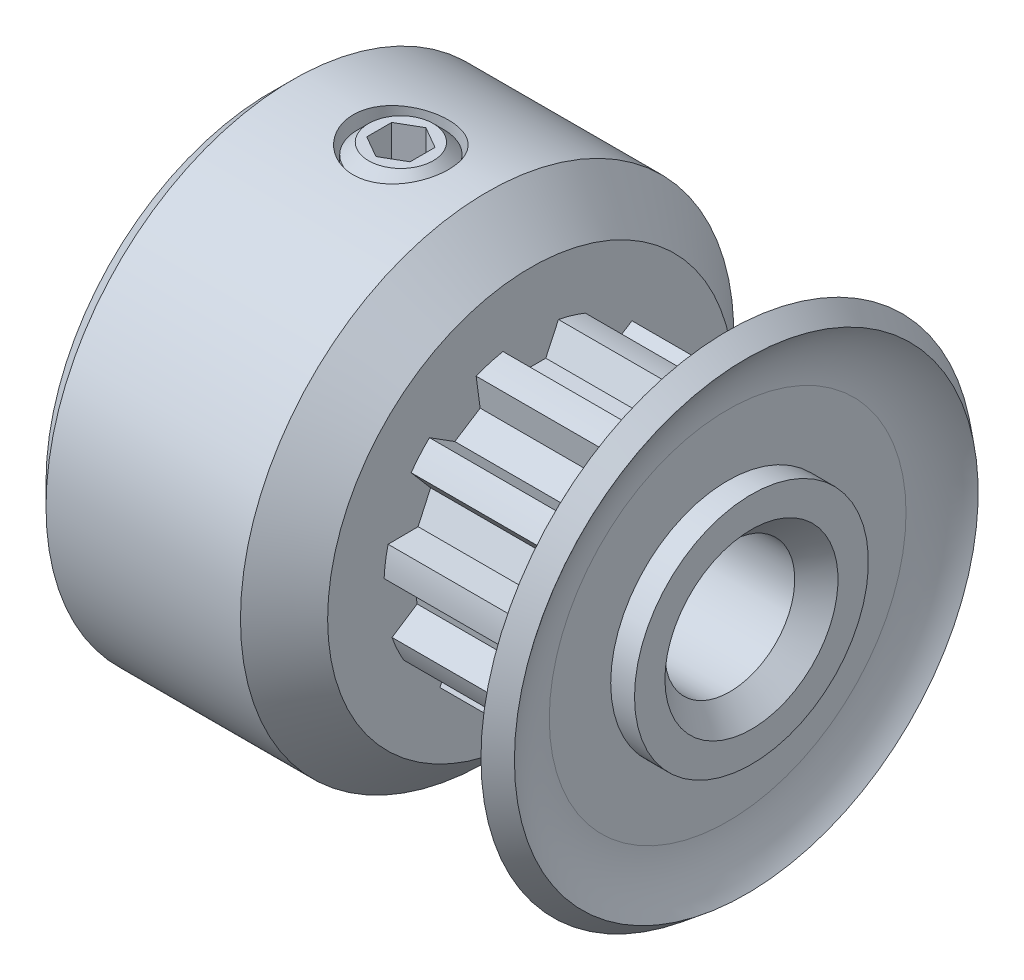
SolidWorks part; units mm, degrees
ref_plane "Front Plane" through (0, 0, 0) normal (0, 0, 1) x (1, 0, 0)
ref_plane "Top Plane" through (0, 0, 0) normal (0, 1, 0) x (1, 0, 0)
ref_plane "Right Plane" through (0, 0, 0) normal (1, 0, 0) x (0, 0, -1)
sketch "Sketch2" plane through (0, 0, 0) normal (1, 0, 0) x (0, 0, -1)
  line L3 (0, 0) -> (0, 2.7245) construction
  line L6 (0, -3.2325) -> (0, -3.55) construction
  line L7 (-0.5715, 3.1816) -> (-0.348, 2.7022)
  line L8 (0.5715, 3.1816) -> (0.348, 2.7022)
  line L9 (-0.5715, 3.1816) -> (-0.6408, 3.3302)
  line L10 (0.5715, 3.1816) -> (0.6408, 3.3302)
  line L12 (-0.348, 2.7022) -> (0.348, 2.7022)
  line L14 (0, 3.2325) -> (0, 3.55) construction
  line L15 (0, 0) -> (0, -1.143) construction
  circle A0 centre (0, 0) radius 3.55 construction
  circle A1 centre (0, 0) radius 2.7245 construction
  circle A2 centre (0, 0) radius 3.2325 construction
  arc A7 (0.6408, 3.3302) -> (-0.6408, 3.3302) centre (0, 0) ccw
  point P5 (0, 3.3912)
  dimension "D3" = 0.3175
  dimension "D1" = 50
sketch "Sketch1" plane through (0, 0, 0) normal (0, 0, 1) x (1, 0, 0)
  line L0 (-5.55, 0) -> (5.55, 0) construction
  line L1 (-5.55, 1.5) -> (5.55, 1.5)
  line L2 (-5.55, 1.5) -> (-5.55, 5.7)
  line L3 (-5.55, 5.7) -> (-0.557, 5.7)
  line L4 (-0.557, 5.7) -> (0.45, 4.693)
  line L5 (0.45, 4.693) -> (0.45, 3.55)
  line L6 (0.45, 3.55) -> (4.45, 3.55)
  line L7 (4.45, 3.55) -> (4.45, 4.1215)
  line L8 (4.45, 3.55) -> (5.55, 3.55) construction
  line L9 (5, 5.7) -> (5.55, 5.7)
  line L10 (5.55, 5.7) -> (5.55, 1.5)
  line L11 (5, 3.55) -> (5, 5.7) construction
  line L12 (-3.0535, 5.7) -> (-3.0535, 1.5) construction
  arc A0 (4.45, 4.1215) -> (5, 5.7) centre (6.9901, 4.1215) cw
  dimension "Bore Size" = 3
  dimension "Overall Width" = 11.1
  dimension "Inside Width" = 4
  dimension "Outside Width" = 5.1
  dimension "Hub Dia" = 11.4
  dimension "OD" = 11.4
  dimension "D1" = 45
  dimension "D2" = 7.1
  dimension "D3" = 1.143
  dimension "D4" = 0.5715
revolve "Revolve1" add sketch "Sketch1" angle 360 mid plane about L0
sketch "Sketch4" plane through (0.45, 0, 0) normal (1, 0, 0) x (0, 0, -1)
  circle A0 centre (0, 0) radius 3.3913
  circle A1 centre (0, 0) radius 3.55 construction
  circle A2 centre (0, 0) radius 3.55
extrude "Cut-Extrude2" cut sketch "Sketch4" along normal up to surface (4 mm away) up to face at (4.45, 0, 3.55)
sketch "Sketch3" plane through (0.45, 0, 0) normal (1, 0, 0) x (0, 0, -1)
  line L2 (-0.5715, 3.1816) -> (-0.348, 2.7022) construction
  line L3 (-0.348, 2.7022) -> (0.348, 2.7022) construction
  line L4 (0.5715, 3.1816) -> (0.348, 2.7022) construction
  line L5 (-0.6408, 3.3302) -> (-0.348, 2.7022)
  line L6 (-0.348, 2.7022) -> (0.348, 2.7022)
  line L7 (0.6408, 3.3302) -> (0.348, 2.7022)
  arc A1 (0.6408, 3.3302) -> (-0.6408, 3.3302) centre (0, 0) ccw construction
  arc A2 (0.6408, 3.3302) -> (-0.6408, 3.3302) centre (0, 0) ccw
extrude "Cut-Extrude1" cut sketch "Sketch3" along normal up to surface (4 mm away)
pattern_circular "CirPattern1" count 11 over 360 about axis through (0, 0, 0) along (1, 0, 0) of "Cut-Extrude1"
sketch "Sketch5" plane through (0, 0, 0) normal (0, 1, 0) x (1, 0, 0)
  line L0 (-5.55, 5.7) -> (-5.55, -5.7) construction
  line L1 (4.45, 4.1215) -> (4.45, -4.1215) construction
  line L2 (5.55, 5.7) -> (5.55, -5.7) construction
  line L3 (0.45, 4.693) -> (0.45, -4.693) construction
  line L4 (4.45, 4.1215) -> (4.45, -4.1215) construction
  line L5 (-5.55, 0) -> (5.55, 0) construction
  line L6 (-5.55, 0) -> (5.55, 0) construction
  point P0 (4.45, 0)
  point P14 (4.45, 0)
  point P15 (0.45, 0)
  dimension "D1" = 11.4
  dimension "D2" = 11.4
sketch "Sketch6" plane through (0, 0, 0) normal (0, 1, 0) x (1, 0, 0)
  line L0 (-5.55, 0) -> (-3.55, 0) construction
  line L1 (-5.55, 5.7) -> (-5.55, -5.7) construction
  line L2 (0.45, 0) -> (-1.55, 0) construction
  line L3 (0.45, -0.348) -> (0.45, 0.348) construction
  line L4 (-3.55, 0) -> (-2.55, 0) construction
  line L5 (-2.55, 0) -> (-3.2571, -0.7071) construction
  circle A0 centre (-2.55, 0) radius 1 construction
  circle A1 centre (-2.55, 0) radius 1.1
  point P13 (-3.2571, -0.7071)
  dimension "D1" = 0.1
  dimension "D2" = 45
  dimension "SS Dia" = 2
extrude "Cut-Extrude3" cut sketch "Sketch6" along normal through all
sketch "Sketch7" plane through (0, 0, 0) normal (0, 0, 1) x (1, 0, 0)
  line L0 (-3.296, 5.7) -> (-2.55, 5.7)
  line L1 (-3.55, 5.446) -> (-3.55, 2.135)
  line L2 (-3.55, 2.135) -> (-3.296, 1.881)
  line L3 (-3.296, 1.881) -> (-2.55, 1.881)
  line L4 (-2.55, 1.881) -> (-2.55, 5.7) construction
  line L6 (-3.55, 5.446) -> (-3.296, 5.7)
  line L7 (-5.55, 5.7) -> (-0.557, 5.7) construction
  line L8 (-2.55, 5.7) -> (-2.55, 1.881)
  point P0 (-3.55, 5.7)
  point P4 (-3.55, 1.881)
  dimension "D2" = 0.381
revolve "Revolve2" add sketch "Sketch7" angle 360 mid plane about L4
sketch "Sketch8" plane through (0, 5.7, 0) normal (0, 1, 0) x (1, 0, 0)
  line L0 (-2.55, 0) -> (-3.55, 0) construction
  line L1 (-2.55, 0.5774) -> (-3.05, 0.2887)
  line L2 (-3.05, 0.2887) -> (-3.05, -0.2887)
  line L3 (-3.05, -0.2887) -> (-2.55, -0.5774)
  line L4 (-2.55, -0.5774) -> (-2.05, -0.2887)
  line L5 (-2.05, -0.2887) -> (-2.05, 0.2887)
  line L6 (-2.05, 0.2887) -> (-2.55, 0.5774)
  circle A0 centre (-2.55, 0) radius 0.5 construction
  point P13 (-3.05, 0)
extrude "Cut-Extrude4" cut sketch "Sketch8" against normal blind 1.016
pattern_circular "CirPattern2" [suppressed] count 2 over 90
pattern_circular "CirPattern3" [suppressed] count 2 over 90
chamfer "Chamfer1" distance 0.5 angle 45 3 edges at (-5.55, 0, 5.7) (-5.55, 0, 1.5) (5.55, 0, 1.5)
sketch "Sketch9" plane through (0, 0, 0) normal (0, 0, 1) x (1, 0, 0)
  line L0 (5.55, 2.7022) -> (5.55, 5.7)
  line L1 (5.55, 5.7) -> (5.55, 1.5) construction
  line L2 (5, 3.55) -> (5, 5.7) construction
  line L3 (5, 4.1215) -> (5, 2.7022)
  line L4 (5, 5.7) -> (5.2124, 5.9678)
  line L5 (5, 2.7022) -> (5.55, 2.7022)
  line L6 (5, 5.7) -> (5.4309, 5.3582)
  line L7 (5.2124, 5.9678) -> (5.55, 5.7)
  line L8 (0.45, 2.7022) -> (5.55, 2.7022) construction
  line L9 (-5.55, 0) -> (5.55, 0) construction
  line L10 (-5.55, 0) -> (5.55, 0) construction
  arc A0 (5, 5.7) -> (4.45, 4.1215) centre (6.9901, 4.1215) ccw construction
  arc A3 (5, 4.1215) -> (5.4309, 5.3582) centre (6.9901, 4.1215) cw
revolve "Cut-Revolve1" cut sketch "Sketch9" angle 360 about L0
equation "\"D3@Sketch2\" = (\"hs@Sketch2\"-\"ht@Sketch2\")/2"
equation "\"D2@Sketch1\" = \"PD@Sketch2\""
equation "\"D3@Sketch1\" = \"hs@Sketch2\""
equation "\"D4@Sketch1\" = \"D3@Sketch1\"/2"
equation "\"D1@Sketch5\"=\"Hub Dia@Sketch1\""
equation "\"D2@Sketch5\"=\"OD@Sketch1\""
